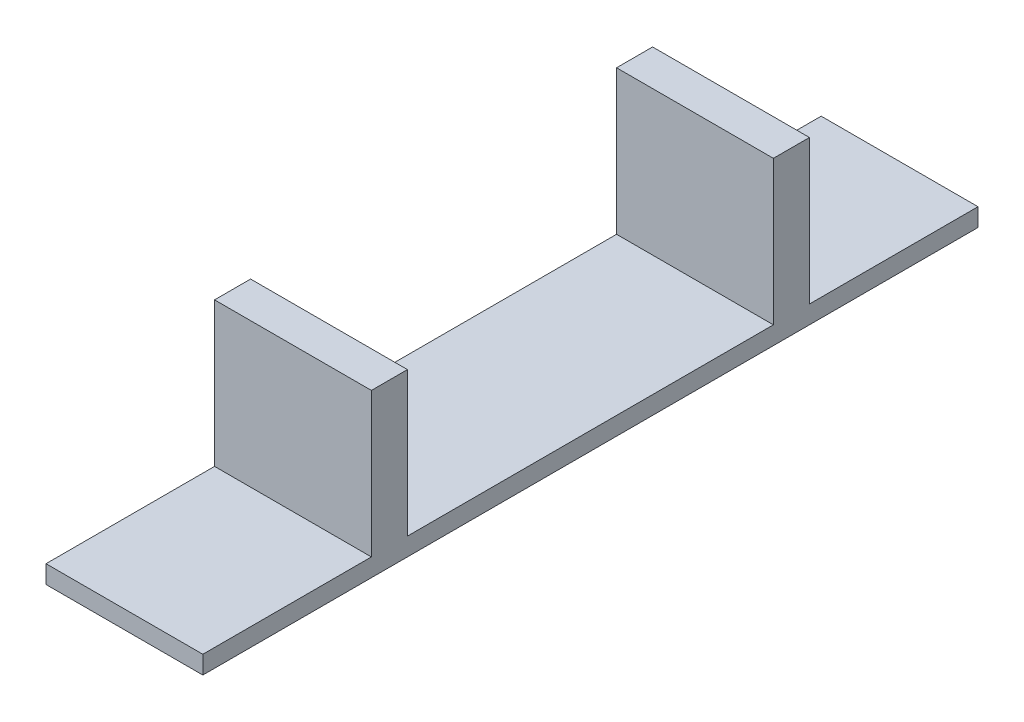
SolidWorks part; units mm, degrees
ref_plane "Alzado" through (0, 0, 0) normal (0, 0, 1) x (1, 0, 0)
ref_plane "Planta" through (0, 0, 0) normal (0, 1, 0) x (1, 0, 0)
ref_plane "Vista lateral" through (0, 0, 0) normal (1, 0, 0) x (0, 0, -1)
sketch "Croquis1" plane through (0, 0, 0) normal (0, 1, 0) x (1, 0, 0)
  line L1 (0, 0) -> (-8.7, 0)
  line L2 (0, 0) -> (0, -43)
  line L3 (0, -43) -> (-8.7, -43)
  line L4 (-8.7, 0) -> (-8.7, -43)
  dimension "D1" = 8.7
  dimension "D2" = 43
extrude "Saliente-Extruir1" add sketch "Croquis1" along normal blind 1
sketch "Croquis2" plane through (0, 1, 0) normal (0, 1, 0) x (1, 0, 0)
  line L0 (-8.7, -21.5) -> (-11.0618, -21.5) construction
  line L1 (-8.7, 0) -> (-8.7, -43) construction
  line L2 (-8.7, -21.5) -> (-8.7, -9.35) construction
  line L3 (0, -43) -> (0, 0) construction
  line L4 (-8.7, -9.35) -> (0, -9.35)
  line L5 (-8.7, -9.35) -> (-8.7, -11.35)
  line L6 (-8.7, -11.35) -> (0, -11.35)
  line L7 (0, -9.35) -> (0, -11.35)
  line L8 (0, -33.65) -> (0, -31.65)
  line L9 (-8.7, -31.65) -> (0, -31.65)
  line L10 (-8.7, -33.65) -> (-8.7, -31.65)
  line L11 (-8.7, -33.65) -> (0, -33.65)
  dimension "D1" = 12.15
  dimension "D2" = 2
extrude "Saliente-Extruir2" add sketch "Croquis2" along normal blind 8
